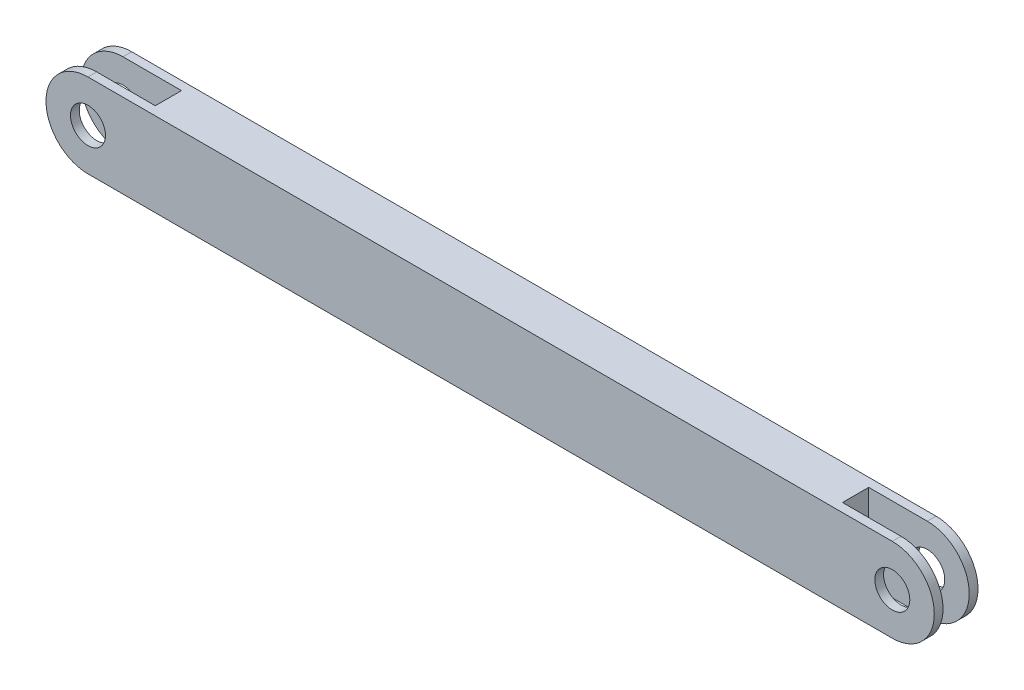
SolidWorks part; units mm, degrees
material "6061 Alloy"
ref_plane "Front Plane" through (0, 0, 0) normal (0, 0, 1) x (1, 0, 0)
ref_plane "Top Plane" through (0, 0, 0) normal (0, 1, 0) x (1, 0, 0)
ref_plane "Right Plane" through (0, 0, 0) normal (1, 0, 0) x (0, 0, -1)
sketch "Sketch1" plane through (0, 0, 0) normal (0, 0, 1) x (1, 0, 0)
  line L0 (0, 0) -> (0, 73217.6577) construction
  line L1 (0, 0) -> (73217.6577, 0) construction
  line L2 (-230, 24) -> (230, 24)
  line L3 (-230, -24) -> (230, -24)
  arc A0 (-230, 24) -> (-230, -24) centre (-230, 0) ccw
  arc A1 (230, 24) -> (230, -24) centre (230, 0) cw
  circle A2 centre (-230, 0) radius 10
  circle A3 centre (230, 0) radius 10
  point P8 (0, 24)
  dimension "D3" = 20
  dimension "D1" = 24
  dimension "D2" = 460
extrude "Boss-Extrude1" add sketch "Sketch1" against normal blind 25
sketch "Sketch3" plane through (0, 0, 0) normal (0, 1, 0) x (1, 0, 0)
  line L0 (-230, 25) -> (-230, 0) construction
  line L1 (-263.5, 20) -> (-196.5, 20)
  line L2 (-263.5, 20) -> (-263.5, 5)
  line L3 (-263.5, 5) -> (-196.5, 5)
  line L4 (-196.5, 20) -> (-196.5, 5)
  line L5 (-263.5, 20) -> (-196.5, 5) construction
  line L6 (-263.5, 5) -> (-196.5, 20) construction
  line L7 (0, 0) -> (0, 50000) construction
  line L8 (0, 0) -> (50000, 0) construction
  line L9 (196.5, 20) -> (196.5, 5)
  line L10 (263.5, 20) -> (196.5, 20)
  line L11 (263.5, 20) -> (263.5, 5)
  line L12 (263.5, 5) -> (196.5, 5)
  line L13 (0, 0) -> (-50000, 0) construction
  point P0 (-230, 12.5)
  dimension "D1" = 15
  dimension "D2" = 67
extrude "Cut-Extrude2" cut sketch "Sketch3" against normal through all and the other way through all
